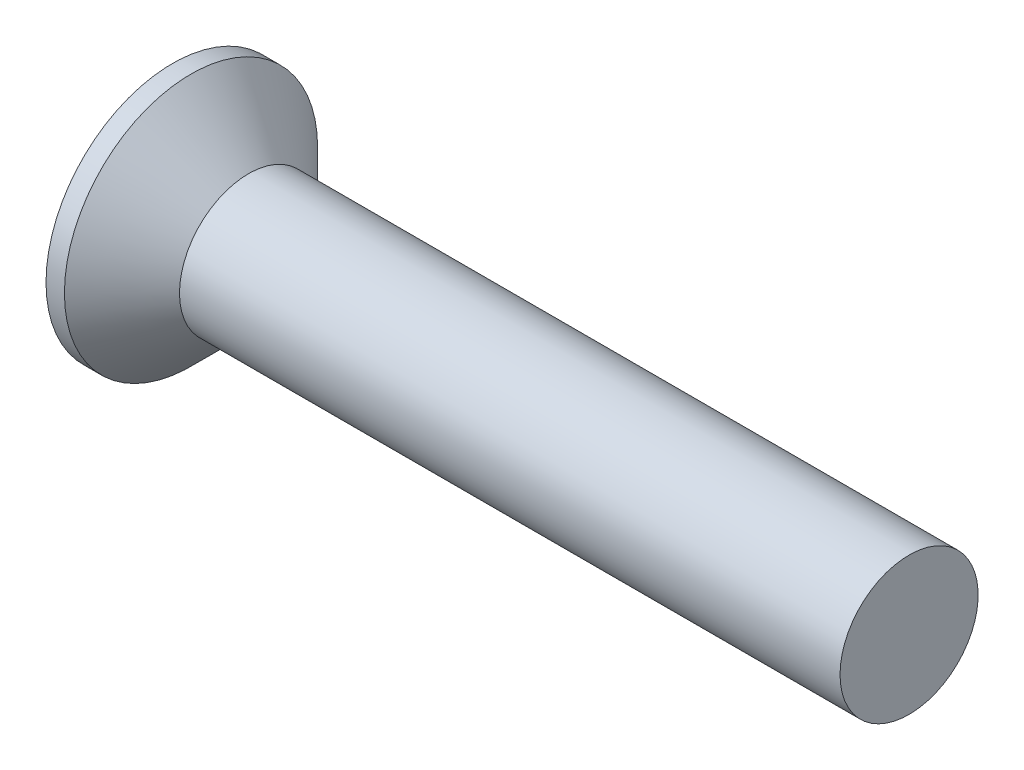
SolidWorks part; units mm, degrees
ref_plane "Plan de face" through (0, 0, 0) normal (0, 0, 1) x (1, 0, 0)
ref_plane "Plan de dessus" through (0, 0, 0) normal (0, 1, 0) x (1, 0, 0)
ref_plane "Plan de droite" through (0, 0, 0) normal (1, 0, 0) x (0, 0, -1)
sketch "Esquisse1" plane through (0, 0, 0) normal (0, 0, 1) x (1, 0, 0)
  line L0 (0, 0) -> (16, 0)
  line L1 (16, 0) -> (16, 1.5)
  line L2 (16, 1.5) -> (1.65, 1.5)
  line L4 (0, 2.75) -> (0, 0)
  line L5 (0, 2.75) -> (0.4, 2.75)
  line L6 (0.4, 2.75) -> (1.65, 1.5)
  dimension "D1" = 16
  dimension "D2" = 1.5
  dimension "D3" = 2.75
  dimension "D4" = 1.65
  dimension "D5" = 45
revolve "Révolution1" add sketch "Esquisse1" angle 360 about L0
equation "\"D3@Esquisse1\"=5.5/2"
